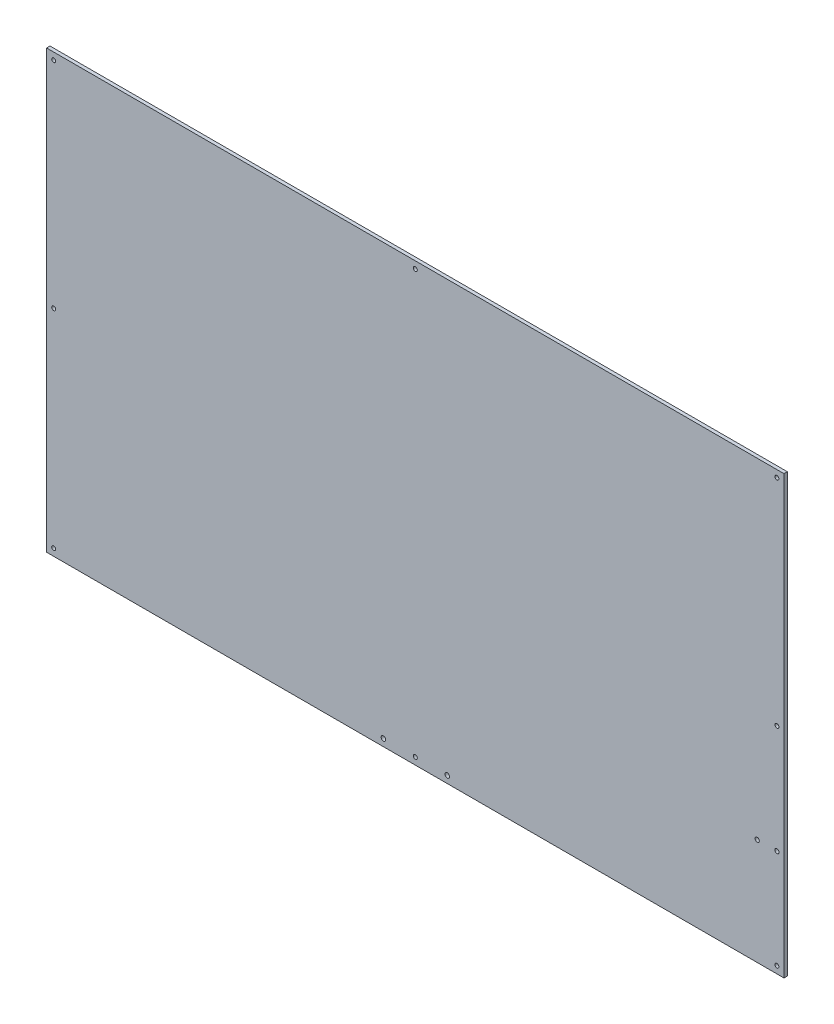
SolidWorks part; units mm, degrees
material "Acrylic (Medium-high impact)"
ref_plane "Front Plane" through (0, 0, 0) normal (0, 0, 1) x (1, 0, 0)
ref_plane "Top Plane" through (0, 0, 0) normal (0, 1, 0) x (1, 0, 0)
ref_plane "Right Plane" through (0, 0, 0) normal (1, 0, 0) x (0, 0, -1)
sketch "Sketch1" plane through (0, 0, 0) normal (0, 0, 1) x (1, 0, 0)
  line L1 (0, 0) -> (1040, 0)
  line L3 (0, 616) -> (1040, 616)
  line L7 (0, 0) -> (0, 616)
  line L11 (1040, 0) -> (1040, 616)
  circle A0 centre (10, 606) radius 2.8
  circle A1 centre (520, 606) radius 2.8
  circle A2 centre (1030, 606) radius 2.8
  circle A3 centre (10, 303) radius 2.8
  circle A4 centre (10, 10) radius 2.8
  circle A5 centre (520, 10) radius 2.8
  circle A6 centre (1030, 10) radius 2.8
  circle A7 centre (1030, 303) radius 2.8
  circle A8 centre (475, 10) radius 3.25
  circle A9 centre (565, 10) radius 3.25
  circle A10 centre (1030, 150) radius 3
  circle A11 centre (1002.2, 150) radius 3
  dimension "D3" = 5.6
  dimension "D4" = 10
  dimension "D5" = 10
  dimension "D20" = 6.5
  dimension "D21" = 6.5
  dimension "D26" = 6
  dimension "D27" = 6
  dimension "D1" = 616
  dimension "D2" = 1040
  dimension "D6" = 10
  dimension "D7" = 313
  dimension "D8" = 10
  dimension "D9" = 10
  dimension "D10" = 10
  dimension "D11" = 510
  dimension "D12" = 10
  dimension "D13" = 510
  dimension "D14" = 10
  dimension "D15" = 313
  dimension "D16" = 10
  dimension "D17" = 10
  dimension "D18" = 10
  dimension "D19" = 10
  dimension "D22" = 10
  dimension "D23" = 10
  dimension "D24" = 45
  dimension "D25" = 45
  dimension "D28" = 10
  dimension "D29" = 27.8
  dimension "D30" = 150
extrude "Boss-Extrude1" add sketch "Sketch1" against normal blind 4.7625
